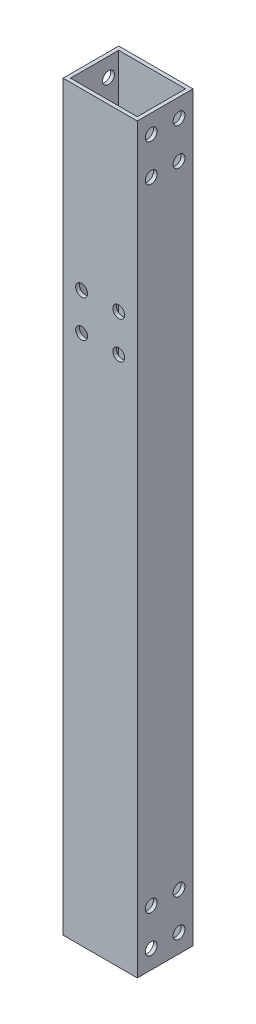
SolidWorks part; units mm, degrees
ref_plane "前视基准面" through (0, 0, 0) normal (0, 0, 1) x (1, 0, 0)
ref_plane "上视基准面" through (0, 0, 0) normal (0, 1, 0) x (1, 0, 0)
ref_plane "右视基准面" through (0, 0, 0) normal (1, 0, 0) x (0, 0, -1)
other "Configuration Table"
sketch "草图1" plane through (0, 0, 0) normal (0, 1, 0) x (1, 0, 0)
  line L1 (-10, -7.5) -> (10, -7.5)
  line L2 (-10, -7.5) -> (-10, 7.5)
  line L3 (-10, 7.5) -> (10, 7.5)
  line L4 (10, -7.5) -> (10, 7.5)
  line L5 (-10, -7.5) -> (10, 7.5) construction
  line L6 (-10, 7.5) -> (10, -7.5) construction
  point P0 (0, 0)
  dimension "D1" = 20
  dimension "D2" = 15
extrude "拉伸-薄壁1" add sketch "草图1" along normal blind 200 thin thin type one direction reverse wall 1
sketch "草图2" plane through (10, 0, 0) normal (1, 0, 0) x (0, 0, -1)
  line L0 (7.5, 200) -> (7.5, 0) construction
  line L1 (-7.5, 200) -> (7.5, 200)
  line L2 (-7.5, 200) -> (-7.5, 180)
  line L3 (-7.5, 180) -> (7.5, 180)
  line L4 (7.5, 200) -> (7.5, 180)
  line L6 (-7.5, 0) -> (7.5, 0)
  line L7 (-7.5, 0) -> (-7.5, 20)
  line L8 (-7.5, 20) -> (7.5, 20)
  line L9 (7.5, 0) -> (7.5, 20)
  dimension "D1" = 20
  dimension "D2" = 20
sketch "草图3" plane through (0, 0, 7.5) normal (0, 0, 1) x (1, 0, 0)
  line L0 (-10, 148) -> (10, 148) construction
  line L3 (0, 148) -> (0, 390.6678) construction
  line L4 (-10, 100) -> (10, 100) construction
  line L5 (-10, 200) -> (-10, 0) construction
  line L6 (10, 200) -> (10, 0) construction
  circle A0 centre (-5, 153) radius 1.6
  circle A1 centre (-5, 143) radius 1.6
  circle A2 centre (5, 143) radius 1.6
  circle A3 centre (5, 153) radius 1.6
  dimension "D1" = 3.2
  dimension "D2" = 10
  dimension "D3" = 10
  dimension "D4" = 48
extrude "切除-拉伸1" cut sketch "草图3" against normal through all
sketch "草图4" plane through (10, 0, 0) normal (1, 0, 0) x (0, 0, -1)
  line L0 (-7.5, 10) -> (7.5, 10) construction
  line L1 (-7.5, 0) -> (-7.5, 20) construction
  line L2 (7.5, 0) -> (7.5, 20) construction
  line L3 (0, 0) -> (0, 20) construction
  line L4 (-7.5, 20) -> (7.5, 20) construction
  line L5 (7.5, 100) -> (-7.5, 100) construction
  line L6 (7.5, 200) -> (7.5, 0) construction
  line L7 (-7.5, 200) -> (-7.5, 0) construction
  line L8 (0, 200) -> (0, 180) construction
  line L9 (-7.5, 190) -> (7.5, 190) construction
  circle A0 centre (-3.75, 5) radius 1.6
  circle A1 centre (-3.75, 15) radius 1.6
  circle A2 centre (3.75, 5) radius 1.6
  circle A3 centre (3.75, 15) radius 1.6
  circle A4 centre (3.75, 185) radius 1.6
  circle A5 centre (3.75, 195) radius 1.6
  circle A6 centre (-3.75, 185) radius 1.6
  circle A7 centre (-3.75, 195) radius 1.6
  dimension "D1" = 3.2
  dimension "D2" = 3.75
  dimension "D3" = 5
extrude "切除-拉伸2" cut sketch "草图4" against normal through all
